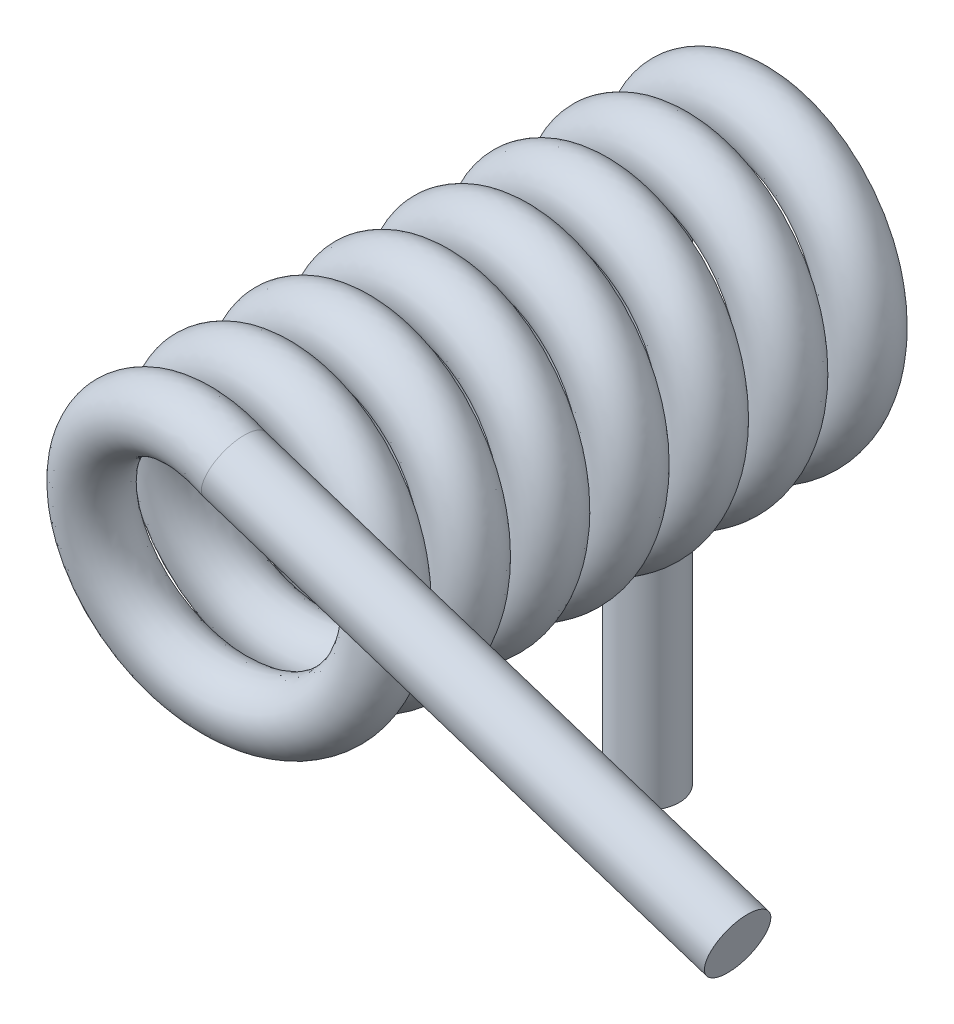
SolidWorks part; units mm, degrees
material "AISI 304"
ref_plane "Front Plane" through (0, 0, 0) normal (0, 0, 1) x (1, 0, 0)
ref_plane "Top Plane" through (0, 0, 0) normal (0, 1, 0) x (1, 0, 0)
ref_plane "Right Plane" through (0, 0, 0) normal (1, 0, 0) x (0, 0, -1)
sketch "Sketch1" plane through (0, 0, 0) normal (0, 0, 1) x (1, 0, 0)
  circle A0 centre (0, 0) radius 6
  dimension "D1" = 12
curve "Helix/Spiral1" pitch 3.75 height 27.375 turns 7.3
ref_plane "Plane1" through (0, 0, 0) normal (0, 1, 0) x (1, 0, 0)
sketch "Sketch2" plane through (0, 0, 0) normal (0, 1, 0) x (1, 0, 0)
  circle A0 centre (-6, 0) radius 1.5
  spline S0 degree 3 poles (-6, 0) (-6, -0.0782) (-5.6832, -0.2362) (-4.331, -0.4719) (-2.3104, -0.708) (0.0667, -0.944) (2.4335, -1.18) (4.4248, -1.4159) (5.7333, -1.6519) (6.1569, -1.8879) (5.6305, -2.1239) (4.2351, -2.3599) (2.1862, -2.5959) (-0.2001, -2.8319) (-2.5555, -3.0679) (-4.5166, -3.3039) (-5.7806, -3.5399) (-6.1526, -3.7759) (-5.5751, -4.0119) (-4.1373, -4.2478) (-2.061, -4.4838) (0.3334, -4.7198) (2.6763, -4.9558) (4.6062, -5.1918) (5.8253, -5.4278) (6.1454, -5.6638) (5.5171, -5.8998) (4.0375, -6.1358) (1.9347, -6.3718) (-0.4666, -6.6078) (-2.7959, -6.8438) (-4.6937, -7.0797) (-5.8672, -7.3157) (-6.1353, -7.5517) (-5.4566, -7.7877) (-3.9358, -8.0237) (-1.8076, -8.2597) (0.5995, -8.4957) (2.9141, -8.7317) (4.779, -8.9677) (5.9064, -9.2037) (6.1223, -9.4397) (5.3934, -9.6756) (3.8322, -9.9116) (1.6797, -10.1476) (-0.7321, -10.3836) (-3.0309, -10.6196) (-4.862, -10.8556) (-5.9428, -11.0916) (-6.1064, -11.3276) (-5.3278, -11.5636) (-3.7269, -11.7996) (-1.5509, -12.0356) (0.8644, -12.2716) (3.1464, -12.5075) (4.9427, -12.7435) (5.9764, -12.9795) (6.0877, -13.2155) (5.2596, -13.4515) (3.6198, -13.6875) (1.4214, -13.9235) (-0.9963, -14.1595) (-3.2603, -14.3955) (-5.0212, -14.6315) (-6.0072, -14.8675) (-6.0661, -15.1034) (-5.189, -15.3394) (-3.511, -15.5754) (-1.2913, -15.8114) (1.1277, -16.0474) (3.3727, -16.2834) (5.0972, -16.5194) (6.0351, -16.7554) (6.0417, -16.9914) (5.1159, -17.2274) (3.4006, -17.4634) (1.1605, -17.6994) (-1.2586, -17.9353) (-3.4836, -18.1713) (-5.1709, -18.4073) (-6.0603, -18.6433) (-6.0144, -18.8793) (-5.0404, -19.1153) (-3.2886, -19.3513) (-1.0292, -19.5873) (1.3889, -19.8233) (3.5928, -20.0593) (5.2422, -20.2953) (6.0826, -20.5313) (5.9843, -20.7672) (4.9626, -21.0032) (3.175, -21.2392) (0.8974, -21.4752) (-1.5186, -21.7112) (-3.7003, -21.9472) (-5.3109, -22.1832) (-6.102, -22.4192) (-5.9514, -22.6552) (-4.8824, -22.8912) (-3.0599, -23.1272) (-0.7652, -23.3631) (1.6475, -23.5991) (3.8061, -23.8351) (5.3772, -24.0711) (6.1186, -24.3071) (5.9157, -24.5431) (4.7999, -24.7791) (2.9434, -25.0151) (0.6327, -25.2511) (-1.7757, -25.4871) (-3.9101, -25.7231) (-5.441, -25.9591) (-6.1323, -26.195) (-5.8772, -26.431) (-4.7154, -26.667) (-2.8249, -26.9031) (-0.502, -27.1388) (1.1068, -27.2968) (1.8541, -27.375) knots 0 0 0 0 0.008621 0.017241 0.025862 0.034483 0.043103 0.051724 0.060345 0.068966 0.077586 0.086207 0.094828 0.103448 0.112069 0.12069 0.12931 0.137931 0.146552 0.155172 0.163793 0.172414 0.181034 0.189655 0.198276 0.206897 0.215517 0.224138 0.232759 0.241379 0.25 0.258621 0.267241 0.275862 0.284483 0.293103 0.301724 0.310345 0.318966 0.327586 0.336207 0.344828 0.353448 0.362069 0.37069 0.37931 0.387931 0.396552 0.405172 0.413793 0.422414 0.431034 0.439655 0.448276 0.456897 0.465517 0.474138 0.482759 0.491379 0.5 0.508621 0.517241 0.525862 0.534483 0.543103 0.551724 0.560345 0.568966 0.577586 0.586207 0.594828 0.603448 0.612069 0.62069 0.62931 0.637931 0.646552 0.655172 0.663793 0.672414 0.681034 0.689655 0.698276 0.706897 0.715517 0.724138 0.732759 0.741379 0.75 0.758621 0.767241 0.775862 0.784483 0.793103 0.801724 0.810345 0.818966 0.827586 0.836207 0.844828 0.853448 0.862069 0.87069 0.87931 0.887931 0.896552 0.905172 0.913793 0.922414 0.931034 0.939655 0.948276 0.956897 0.965517 0.974138 0.982759 0.991379 1 1 1 1 construction
  point P3 (-6, 0)
  dimension "D1" = 3
  dimension "D2" = 6
sweep "Sweep1" add profiles "Sketch2" path "Helix/Spiral1"
ref_plane "Plane2" through (0, 0, 0) normal (0, -1, 0) x (-1, 0, 0)
sketch "Sketch3" plane through (0, 0, 0) normal (0, -1, 0) x (-1, 0, 0)
  circle A0 centre (6, 0) radius 1.5
  spline S0 degree 3 poles (6, 0) (6, -0.0782) (5.6832, -0.2362) (4.331, -0.4719) (2.3104, -0.708) (-0.0667, -0.944) (-2.4335, -1.18) (-4.4248, -1.4159) (-5.7333, -1.6519) (-6.1569, -1.8879) (-5.6305, -2.1239) (-4.2351, -2.3599) (-2.1862, -2.5959) (0.2001, -2.8319) (2.5555, -3.0679) (4.5166, -3.3039) (5.7806, -3.5399) (6.1526, -3.7759) (5.5751, -4.0119) (4.1373, -4.2478) (2.061, -4.4838) (-0.3334, -4.7198) (-2.6763, -4.9558) (-4.6062, -5.1918) (-5.8253, -5.4278) (-6.1454, -5.6638) (-5.5171, -5.8998) (-4.0375, -6.1358) (-1.9347, -6.3718) (0.4666, -6.6078) (2.7959, -6.8438) (4.6937, -7.0797) (5.8672, -7.3157) (6.1353, -7.5517) (5.4566, -7.7877) (3.9358, -8.0237) (1.8076, -8.2597) (-0.5995, -8.4957) (-2.9141, -8.7317) (-4.779, -8.9677) (-5.9064, -9.2037) (-6.1223, -9.4397) (-5.3934, -9.6756) (-3.8322, -9.9116) (-1.6797, -10.1476) (0.7321, -10.3836) (3.0309, -10.6196) (4.862, -10.8556) (5.9428, -11.0916) (6.1064, -11.3276) (5.3278, -11.5636) (3.7269, -11.7996) (1.5509, -12.0356) (-0.8644, -12.2716) (-3.1464, -12.5075) (-4.9427, -12.7435) (-5.9764, -12.9795) (-6.0877, -13.2155) (-5.2596, -13.4515) (-3.6198, -13.6875) (-1.4214, -13.9235) (0.9963, -14.1595) (3.2603, -14.3955) (5.0212, -14.6315) (6.0072, -14.8675) (6.0661, -15.1034) (5.189, -15.3394) (3.511, -15.5754) (1.2913, -15.8114) (-1.1277, -16.0474) (-3.3727, -16.2834) (-5.0972, -16.5194) (-6.0351, -16.7554) (-6.0417, -16.9914) (-5.1159, -17.2274) (-3.4006, -17.4634) (-1.1605, -17.6994) (1.2586, -17.9353) (3.4836, -18.1713) (5.1709, -18.4073) (6.0603, -18.6433) (6.0144, -18.8793) (5.0404, -19.1153) (3.2886, -19.3513) (1.0292, -19.5873) (-1.3889, -19.8233) (-3.5928, -20.0593) (-5.2422, -20.2953) (-6.0826, -20.5313) (-5.9843, -20.7672) (-4.9626, -21.0032) (-3.175, -21.2392) (-0.8974, -21.4752) (1.5186, -21.7112) (3.7003, -21.9472) (5.3109, -22.1832) (6.102, -22.4192) (5.9514, -22.6552) (4.8824, -22.8912) (3.0599, -23.1272) (0.7652, -23.3631) (-1.6475, -23.5991) (-3.8061, -23.8351) (-5.3772, -24.0711) (-6.1186, -24.3071) (-5.9157, -24.5431) (-4.7999, -24.7791) (-2.9434, -25.0151) (-0.6327, -25.2511) (1.7757, -25.4871) (3.9101, -25.7231) (5.441, -25.9591) (6.1323, -26.195) (5.8772, -26.431) (4.7154, -26.667) (2.8249, -26.9031) (0.502, -27.1388) (-1.1068, -27.2968) (-1.8541, -27.375) knots 0 0 0 0 0.008621 0.017241 0.025862 0.034483 0.043103 0.051724 0.060345 0.068966 0.077586 0.086207 0.094828 0.103448 0.112069 0.12069 0.12931 0.137931 0.146552 0.155172 0.163793 0.172414 0.181034 0.189655 0.198276 0.206897 0.215517 0.224138 0.232759 0.241379 0.25 0.258621 0.267241 0.275862 0.284483 0.293103 0.301724 0.310345 0.318966 0.327586 0.336207 0.344828 0.353448 0.362069 0.37069 0.37931 0.387931 0.396552 0.405172 0.413793 0.422414 0.431034 0.439655 0.448276 0.456897 0.465517 0.474138 0.482759 0.491379 0.5 0.508621 0.517241 0.525862 0.534483 0.543103 0.551724 0.560345 0.568966 0.577586 0.586207 0.594828 0.603448 0.612069 0.62069 0.62931 0.637931 0.646552 0.655172 0.663793 0.672414 0.681034 0.689655 0.698276 0.706897 0.715517 0.724138 0.732759 0.741379 0.75 0.758621 0.767241 0.775862 0.784483 0.793103 0.801724 0.810345 0.818966 0.827586 0.836207 0.844828 0.853448 0.862069 0.87069 0.87931 0.887931 0.896552 0.905172 0.913793 0.922414 0.931034 0.939655 0.948276 0.956897 0.965517 0.974138 0.982759 0.991379 1 1 1 1 construction
  dimension "D1" = 3
extrude "Boss-Extrude1" add sketch "Sketch3" along normal blind 25
ref_plane "Plane3" through (0, 0, 0) normal (0.9511, -0.309, 0) x (0, 0, -1)
sketch "Sketch4" plane through (0, 0, 0) normal (0.9511, -0.309, 0) x (0, 0, -1)
  circle A0 centre (-27.3753, 6) radius 1.5
  dimension "D1" = 3
sketch "Sketch6" plane through (0, -25, 0) normal (0, -1, 0) x (1, 0, 0)
  circle A0 centre (-6, 0) radius 1.5
  point P0 (-6, 0)
  dimension "D1" = 3
ref_plane "Plane4" through (0, 0, -1.5) normal (0, 0, -1) x (-1, 0, 0)
extrude "Boss-Extrude2" add sketch "Sketch4" along normal blind 25 contours A0
sketch "Sketch7" plane through (23.7765, -7.7253, 0) normal (0.9511, -0.309, 0) x (0, 0, -1)
  circle A1 centre (-27.3753, 6) radius 1.5
  circle A2 centre (-27.3753, 6) radius 1.5
  point P1 (-27.3753, 6)
  dimension "D1" = 0
